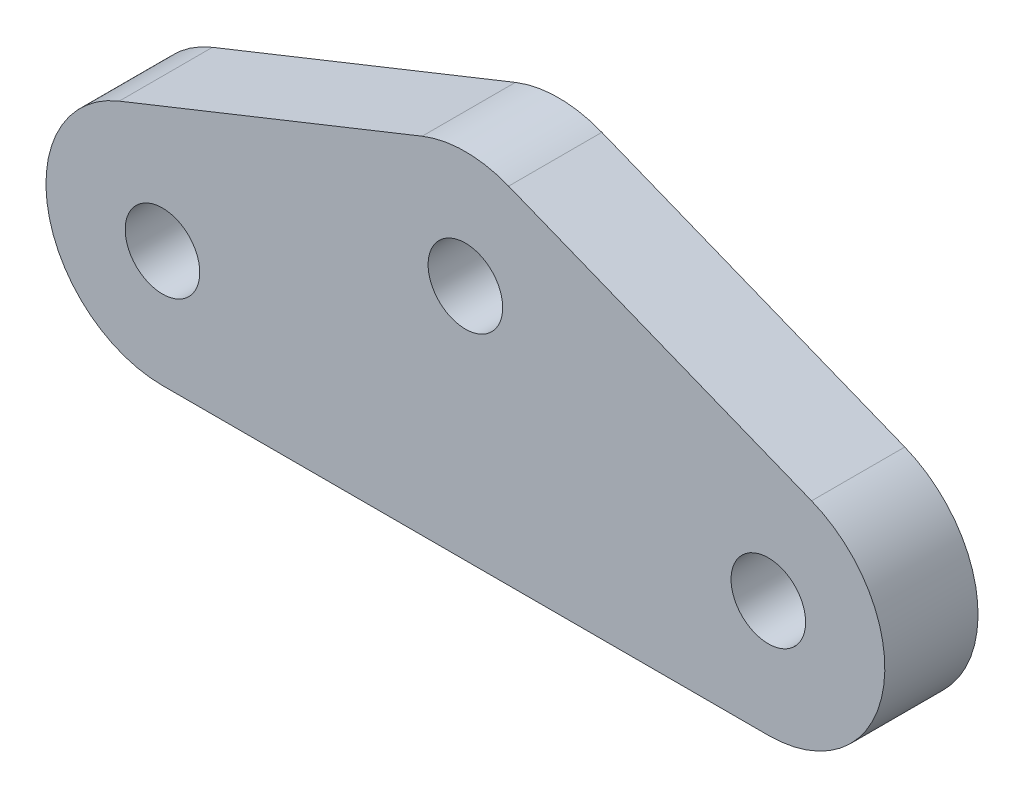
SolidWorks part; units mm, degrees
ref_plane "正面" through (0, 0, 0) normal (0, 0, 1) x (1, 0, 0)
ref_plane "平面" through (0, 0, 0) normal (0, 1, 0) x (1, 0, 0)
ref_plane "右側面" through (0, 0, 0) normal (1, 0, 0) x (0, 0, -1)
sketch "ｽｹｯﾁ2" plane through (0, 0, 0) normal (0, 0, 1) x (1, 0, 0)
  line L0 (-14.8558, 4.6429) -> (-1.8558, 9.839)
  line L1 (1.8558, 9.839) -> (14.8558, 4.6429)
  line L2 (13, -5) -> (-13, -5)
  arc A0 (-14.8558, 4.6429) -> (-13, -5) centre (-13, 0) ccw
  arc A1 (1.8558, 9.839) -> (-1.8558, 9.839) centre (0, 5.1962) ccw
  arc A2 (13, -5) -> (14.8558, 4.6429) centre (13, 0) ccw
  circle A3 centre (-13, 0) radius 1.6
  circle A4 centre (0, 5.1962) radius 1.6
  circle A5 centre (13, 0) radius 1.6
  dimension "D3" = 5
  dimension "D4" = 3.2
  dimension "D1" = 14
  dimension "26" = 26
extrude "ﾎﾞｽ - 押し出し1" add sketch "ｽｹｯﾁ2" along normal blind 4
